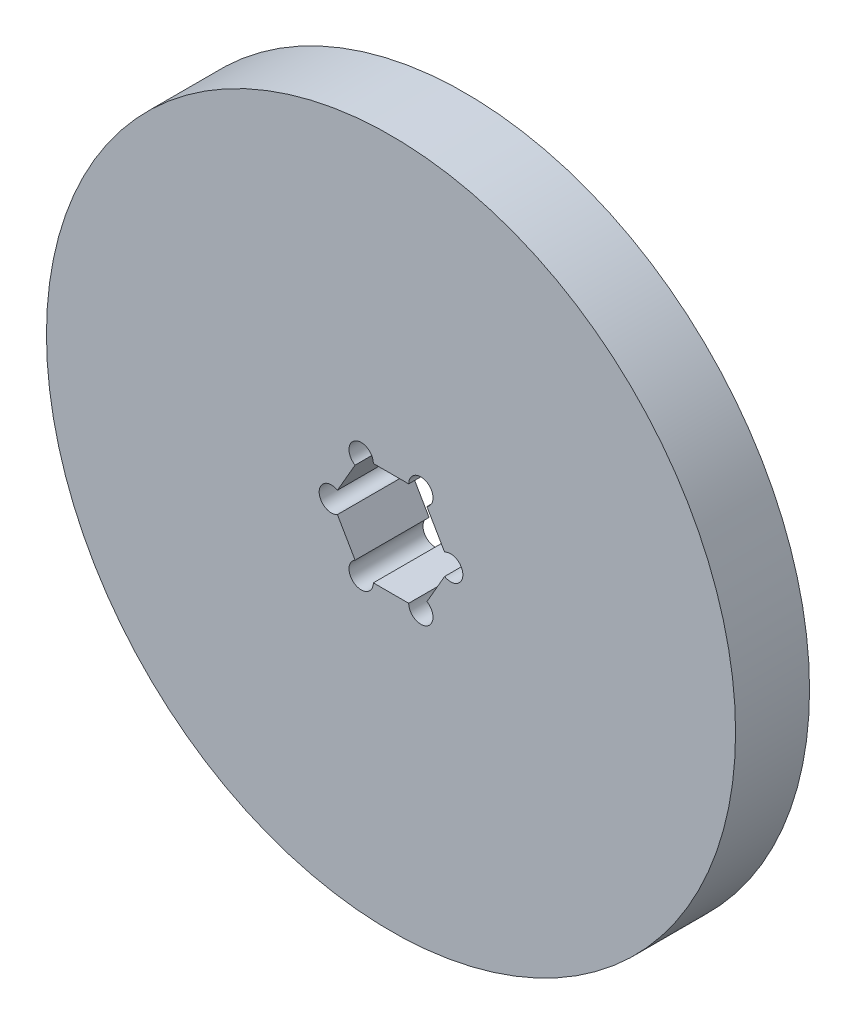
SolidWorks part; units mm, degrees
ref_plane "Front Plane" through (0, 0, 0) normal (0, 0, 1) x (1, 0, 0)
ref_plane "Top Plane" through (0, 0, 0) normal (0, 1, 0) x (1, 0, 0)
ref_plane "Right Plane" through (0, 0, 0) normal (1, 0, 0) x (0, 0, -1)
sketch "Sketch1" plane through (0, 0, 0) normal (0, 0, 1) x (1, 0, 0)
  line L1 (7.479, 0) -> (3.7395, 6.477)
  line L2 (3.7395, 6.477) -> (-3.7395, 6.477)
  line L3 (-3.7395, 6.477) -> (-7.479, 0)
  line L4 (-7.479, 0) -> (-3.7395, -6.477)
  line L5 (-3.7395, -6.477) -> (3.7395, -6.477)
  line L6 (3.7395, -6.477) -> (7.479, 0)
  circle A0 centre (0, 0) radius 6.477 construction
  circle A1 centre (-3.7395, 6.477) radius 1.524
  circle A2 centre (3.7395, 6.477) radius 1.524
  circle A3 centre (7.479, 0) radius 1.524
  circle A4 centre (3.7395, -6.477) radius 1.524
  circle A5 centre (-3.7395, -6.477) radius 1.524
  circle A6 centre (-7.479, 0) radius 1.524
  circle A7 centre (0, 0) radius 43.18
  dimension "D1" = 12.954
  dimension "D2" = 3.048
  dimension "D3" = 86.36
extrude "Boss-Extrude1" add sketch "Sketch1" along normal blind 9.271 contours A7 A6 L3 A1 L2 A2 L1 A3 L6 A4 L5 A5 L4
